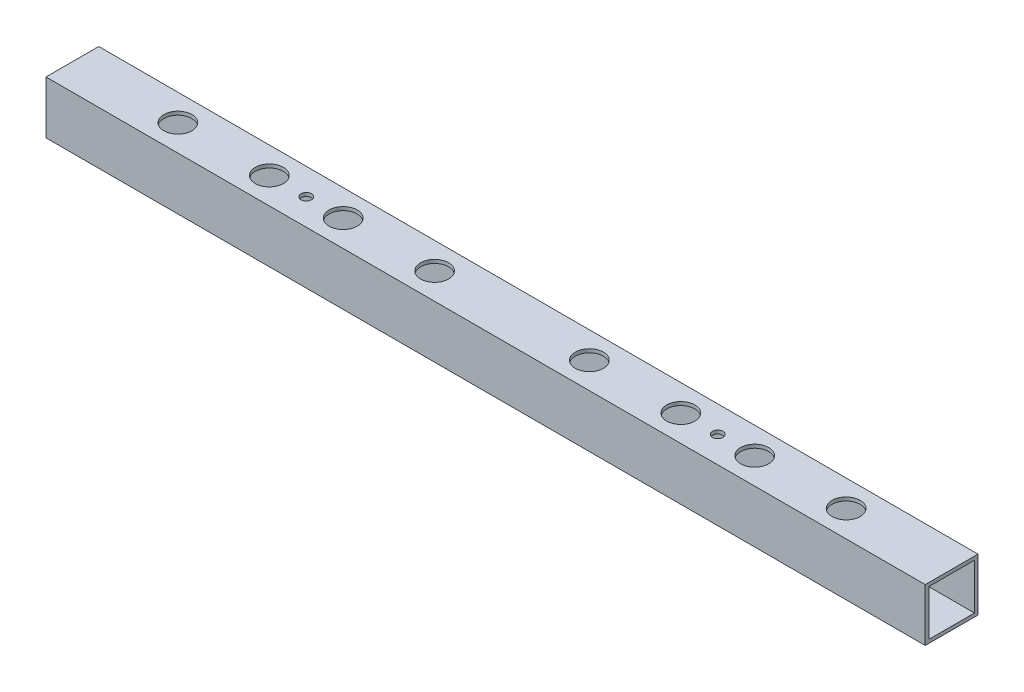
SolidWorks part; units mm, degrees
ref_plane "前视基准面" through (0, 0, 0) normal (0, 0, 1) x (1, 0, 0)
ref_plane "上视基准面" through (0, 0, 0) normal (0, 1, 0) x (1, 0, 0)
ref_plane "右视基准面" through (0, 0, 0) normal (1, 0, 0) x (0, 0, -1)
sketch "草图1" plane through (0, 0, 0) normal (1, 0, 0) x (0, 0, -1)
  line L0 (-6.5, 6.5) -> (6.5, 6.5)
  line L1 (-7.5, -7.5) -> (7.5, -7.5)
  line L2 (-7.5, -7.5) -> (-7.5, 7.5)
  line L3 (-7.5, 7.5) -> (7.5, 7.5)
  line L4 (7.5, -7.5) -> (7.5, 7.5)
  line L5 (-7.5, -7.5) -> (7.5, 7.5) construction
  line L6 (-7.5, 7.5) -> (7.5, -7.5) construction
  line L7 (6.5, -6.5) -> (6.5, 6.5)
  line L8 (-6.5, -6.5) -> (6.5, -6.5)
  line L9 (-6.5, -6.5) -> (-6.5, 6.5)
  point P0 (0, 0)
  dimension "D1" = 15
  dimension "D2" = 15
  dimension "D3" = 1
extrude "凸台-拉伸1" add sketch "草图1" along normal blind 250
sketch "草图2" plane through (0, 7.5, 0) normal (0, 1, 0) x (1, 0, 0)
  line L0 (0, 7.5) -> (0, -7.5) construction
  line L1 (125, -17.4102) -> (125, 42.389) construction
  circle A0 centre (30, 0) radius 1.5
  circle A1 centre (56, 0) radius 1.5
  circle A2 centre (66.5, 0) radius 1.5
  circle A3 centre (103, 0) radius 1.5
  circle A4 centre (77, 0) radius 1.5
  circle A5 centre (173, 0) radius 1.5
  circle A6 centre (147, 0) radius 1.5
  circle A7 centre (183.5, 0) radius 1.5
  circle A8 centre (194, 0) radius 1.5
  circle A9 centre (220, 0) radius 1.5
  dimension "D1" = 77
  dimension "D2" = 103
  dimension "D3" = 66.5
  dimension "D4" = 56
  dimension "D5" = 30
extrude "切除-拉伸1" cut sketch "草图2" against normal blind 250
sketch "草图3" plane through (0, 7.5, 0) normal (0, 1, 0) x (1, 0, 0)
  line L0 (125, -21.8879) -> (125, 34.7414) construction
  circle A0 centre (30, 0) radius 4
  circle A1 centre (56, 0) radius 4
  circle A2 centre (103, 0) radius 4
  circle A3 centre (173, 0) radius 4
  circle A4 centre (77, 0) radius 4
  circle A5 centre (147, 0) radius 4
  circle A6 centre (194, 0) radius 4
  circle A7 centre (220, 0) radius 4
extrude "切除-拉伸2" cut sketch "草图3" against normal blind 10
sketch "草图4" plane through (0, -7.5, 0) normal (0, -1, 0) x (1, 0, 0)
  circle A0 centre (66.5, 0) radius 4
  circle A1 centre (183.5, 0) radius 4
extrude "切除-拉伸3" cut sketch "草图4" against normal blind 10
